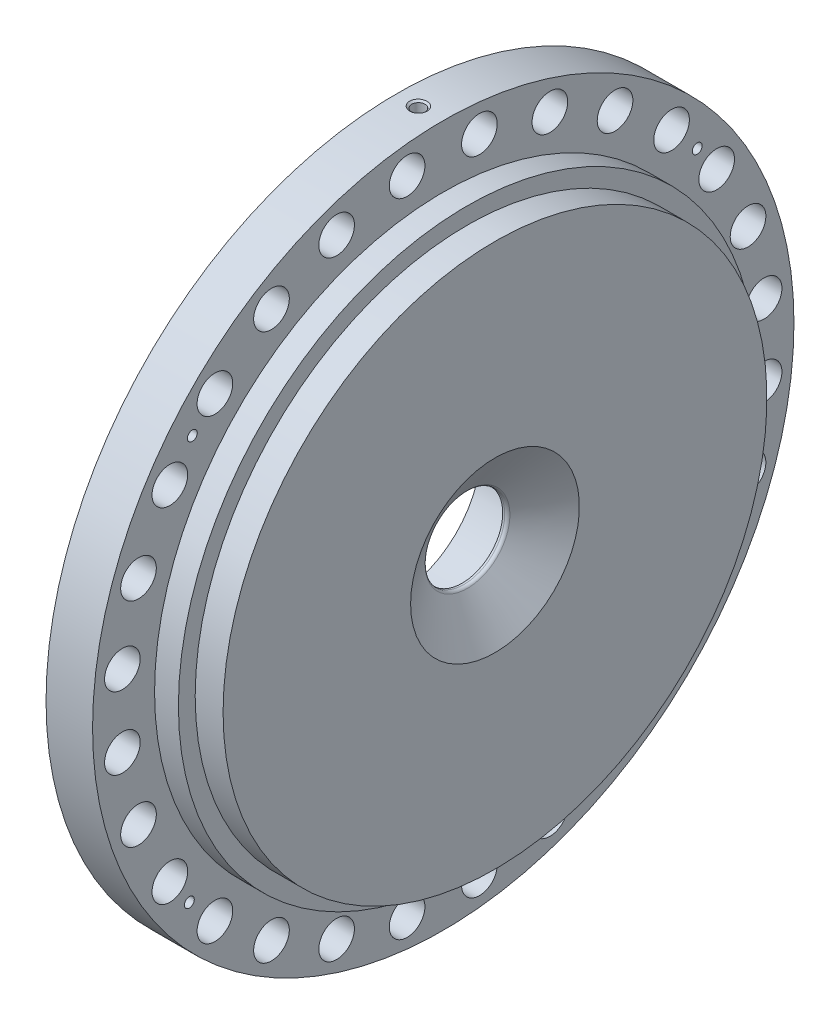
SolidWorks part; units mm, degrees
other "Markup1"
sketch "Sketch22" plane through (-5.9944, 281.051, 281.051) normal (-0.6486, 0.3883, 0.6546) x (0.7525, 0.1979, 0.6281)
material "CD4Mc-U Duplex Stainless Steel"
ref_plane "Front Plane" through (0, 0, 0) normal (0, 0, 1) x (1, 0, 0)
ref_plane "Top Plane" through (0, 0, 0) normal (0, 1, 0) x (1, 0, 0)
ref_plane "Right Plane" through (0, 0, 0) normal (1, 0, 0) x (0, 0, -1)
sketch "Sketch1" plane through (0, 0, 0) normal (0, 0, 1) x (1, 0, 0)
  line L13 (-4.7752, 67.5132) -> (-4.7752, 180.9496)
  line L14 (-4.7752, 281.051) -> (32.512, 281.051)
  line L15 (32.512, 281.051) -> (32.512, 231.3686)
  line L16 (32.512, 231.3686) -> (51.6128, 231.3686)
  line L17 (51.6128, 231.3686) -> (51.6128, 217.9066)
  line L18 (51.6128, 217.9066) -> (73.9648, 217.9066)
  line L19 (73.9648, 217.9066) -> (73.9648, 67.6275)
  line L22 (0, 0) -> (159.4613, 0) construction
  line L27 (-4.7752, 228.9937) -> (0, 228.9937)
  line L28 (0, 228.9937) -> (0, 180.9496)
  line L29 (0, 180.9496) -> (-4.7752, 180.9496)
  line L30 (-4.7752, 228.9937) -> (-4.7752, 281.051)
  line L32 (-4.7752, 67.5132) -> (47.625, 67.5132)
  line L35 (47.625, 67.5132) -> (47.625, 32.5628)
  line L36 (47.625, 32.5628) -> (49.2384, 32.5628)
  line L37 (51.8928, 33.9958) -> (73.9648, 67.6275)
  arc A0 (49.2384, 32.5628) -> (51.8928, 33.9958) centre (49.2384, 35.7378) ccw
  point P18 (50.9524, 32.5628)
  dimension "D10" = 3.175
  dimension "D1" = 78.74
  dimension "D2" = 41.4528
  dimension "D3" = 19.1008
  dimension "D4" = 3.3274
  dimension "D5" = 281.051
  dimension "D6" = 228.9937
  dimension "D7" = 231.3686
  dimension "D8" = 217.9066
  dimension "D9" = 180.9496
  dimension "D11" = 4.7752
  dimension "D12" = 32.5628
  dimension "D13" = 52.4002
  dimension "D14" = 67.5132
  dimension "D16" = 67.6275
revolve "Revolve1" add sketch "Sketch1" angle 360 about L22
sketch "Sketch4" plane through (-4.7752, 0, 0) normal (-1, 0, 0) x (0, 0, 1)
  line L0 (0, 0) -> (0, 281.051) construction
  line L1 (0, 0) -> (28.9721, 257.1355) construction
  circle A1 centre (28.9721, 257.1355) radius 14.2875
  circle A2 centre (0, 0) radius 258.7625 construction
  dimension "D2" = 28.575
  dimension "D3" = 517.525
  dimension "D1" = 6.429
extrude "Cut-Extrude1" cut sketch "Sketch4" against normal through all
pattern_circular "CirPattern2" count 28 over 360 about axis through (0, 0, 0) along (1, 0, 0) of "Cut-Extrude1"
sketch "Sketch5" plane through (0, 0, 0) normal (-1, 0, 0) x (0, 0, 1)
  line L0 (0, 0) -> (53.4138, 199.3429) construction
  line L2 (0, 0) -> (0, 281.051) construction
  circle A0 centre (0, 0) radius 206.375 construction
  circle A1 centre (53.4138, 199.3429) radius 9.525
  circle A3 centre (0, 0) radius 281.051 construction
  dimension "D1" = 412.75
  dimension "D3" = 19.05
  dimension "D2" = 15
hole_wizard "3/4-10 Tapped Hole1" positions "Sketch7" profile "Sketch8" tap size "3/4-10" standard "ANSI Inch"
sketch "Sketch7" plane through (0, 0, 0) normal (-1, 0, 0) x (0, 0, 1)
  point P0 (53.4138, 199.3429)
sketch "Sketch8" plane through (0, 199.3429, 53.4138) normal (0, 1, 0) x (0, 0, 1)
  line L0 (0, 0) -> (0, 30.4074)
  line L1 (0, 30.4074) -> (8.3337, 25.4)
  line L2 (8.3337, 25.4) -> (8.3337, 1.8263)
  line L3 (8.3337, 1.8263) -> (10.16, 0)
  line L5 (10.16, 0) -> (0, 0)
  line L6 (-8.3337, 1.8263) -> (-10.16, 0) construction
  line L10 (0, 30.4074) -> (-8.3337, 25.4) construction
  line L11 (0, -6.35) -> (0, 107.95) construction
  dimension "Tap Drill Dia." = 16.6675
  dimension "Tap Drill Depth" = 25.4
  dimension "Near C'Sink Dia." = 20.32
  dimension "Near C'Sink Angle" = 90
  dimension "Drill Angle" = 118
cosmetic thread "Hole Thread2" parameters "D1"=12.7, "D2"=19.05
pattern_circular "CirPattern3" count 12 over 360 about axis through (0, 0, 0) along (1, 0, 0) of "3/4-10 Tapped Hole1"
cosmetic thread "Hole Thread3" parameters "D1"=12.7, "D2"=19.05
cosmetic thread "Hole Thread4" parameters "D1"=12.7, "D2"=19.05
cosmetic thread "Hole Thread5" parameters "D1"=12.7, "D2"=19.05
cosmetic thread "Hole Thread6" parameters "D1"=12.7, "D2"=19.05
cosmetic thread "Hole Thread7" parameters "D1"=12.7, "D2"=19.05
cosmetic thread "Hole Thread8" parameters "D1"=12.7, "D2"=19.05
cosmetic thread "Hole Thread9" parameters "D1"=12.7, "D2"=19.05
cosmetic thread "Hole Thread10" parameters "D1"=12.7, "D2"=19.05
cosmetic thread "Hole Thread11" parameters "D1"=12.7, "D2"=19.05
cosmetic thread "Hole Thread12" parameters "D1"=12.7, "D2"=19.05
cosmetic thread "Hole Thread13" parameters "D1"=12.7, "D2"=19.05
sketch "Sketch9" plane through (-4.7752, 0, 0) normal (-1, 0, 0) x (0, 0, 1)
  line L0 (0, 0) -> (0, 94.996) construction
  line L1 (0, 0) -> (67.1723, 67.1723) construction
  circle A0 centre (0, 0) radius 94.996 construction
  circle A1 centre (67.1723, 67.1723) radius 11.1125
  dimension "D1" = 189.992
  dimension "D3" = 22.225
  dimension "D2" = 45
hole_wizard "7/8-9 Tapped Hole1" positions "3DSketch1" profile "Sketch10" tap size "7/8-9" standard "ANSI Inch"
sketch3d "3DSketch1"
  point P0 (-4.7752, 67.1723, 67.1723)
sketch "Sketch10" plane through (-4.7752, 67.1723, 67.1723) normal (0, 1, 0) x (0, 0, 1)
  line L0 (0, 0) -> (0, 31.2422)
  line L1 (0, 31.2422) -> (9.7231, 25.4)
  line L2 (9.7231, 25.4) -> (9.7231, 2.0244)
  line L3 (9.7231, 2.0244) -> (11.7475, 0)
  line L5 (11.7475, 0) -> (0, 0)
  line L6 (-9.7231, 2.0244) -> (-11.7475, 0) construction
  line L10 (0, 31.2422) -> (-9.7231, 25.4) construction
  line L11 (0, -6.35) -> (0, 107.95) construction
  dimension "Tap Drill Dia." = 19.4462
  dimension "Tap Drill Depth" = 25.4
  dimension "Near C'Sink Dia." = 23.495
  dimension "Near C'Sink Angle" = 90
  dimension "Drill Angle" = 118
cosmetic thread "Hole Thread14" parameters "D1"=44.45, "D2"=22.225
pattern_circular "CirPattern4" count 4 over 360 about axis through (0, 0, 0) along (1, 0, 0) of "7/8-9 Tapped Hole1"
cosmetic thread "Hole Thread15" parameters "D1"=44.45, "D2"=22.225
cosmetic thread "Hole Thread16" parameters "D1"=44.45, "D2"=22.225
cosmetic thread "Hole Thread17" parameters "D1"=44.45, "D2"=22.225
sketch "Sketch11" plane through (-4.7752, 0, 0) normal (-1, 0, 0) x (0, 0, 1)
  line L0 (0, 0) -> (201.0962, 162.8445) construction
  line L1 (0, 0) -> (258.7625, 0) construction
  circle A0 centre (0, 0) radius 258.7625 construction
  circle A2 centre (201.0962, 162.8445) radius 4.7625
  dimension "D1" = 517.525
  dimension "D3" = 9.525
  dimension "D2" = 39
hole_wizard "Tap Drill for 3/8-16 Tap1" positions "3DSketch9" profile "Sketch21" hole size "3/8-16" standard "ANSI Inch"
sketch3d "3DSketch9"
  point P0 (-4.7752, 162.8445, 201.0962)
sketch "Sketch21" plane through (-4.7752, 162.8445, 201.0962) normal (0, 1, 0) x (0, 0, 1)
  line L0 (0, 0) -> (0, 43.0247)
  line L1 (0, 43.0247) -> (3.9687, 40.64)
  line L2 (3.9687, 40.64) -> (3.9687, 0.635)
  line L3 (3.9687, 0.635) -> (4.6037, 0)
  line L5 (4.6037, 0) -> (0, 0)
  line L6 (-3.9687, 0.635) -> (-4.6037, 0) construction
  line L10 (0, 43.0247) -> (-3.9688, 40.64) construction
  line L11 (0, -6.35) -> (0, 107.95) construction
  dimension "Hole Dia." = 7.9375
  dimension "Hole Depth" = 40.64
  dimension "Near C'Sink Dia." = 9.2075
  dimension "Near C'Sink Angle" = 90
  dimension "Drill Angle" = 118
ref_plane "Plane2" through (0, 281.051, 0) normal (0, 1, 0) x (1, 0, 0)
sketch "Sketch20" plane through (0, 281.051, 0) normal (0, 1, 0) x (1, 0, 0)
  line L0 (-4.7752, 0) -> (12.5984, 0) construction
  line L1 (-4.7752, 281.051) -> (-4.7752, -281.051) construction
  dimension "D1" = 17.3736
pattern_circular "CirPattern5" count 56 over 360 about axis through (0, 0, 0) along (-1, 0, 0) skipping 1, 2, 3, 4, 5, 6, 7, 8, 9, 10, 11, 12, 13, 14, 15, 17, 18, 19, 20, 21, 22, 23, 24, 25, 26, 27, 29, 30, 31, 32, 33, 34, 35, 36, 37, 38, 39, 40, 41, 42, 43, 45, 46, 47, 48, 49, 50, 51, 52, 53, 54, 55 of "Tap Drill for 3/8-16 Tap1"
hole_wizard "1/2-13 Tapped Hole4" positions "3DSketch8" profile "Sketch19" tap size "1/2-13" standard "ANSI Inch"
sketch3d "3DSketch8"
  point P0 (12.5984, 281.051, 0)
sketch "Sketch19" plane through (12.5984, 281.051, 0) normal (1, 0, 0) x (0, 0, 1)
  line L0 (0, 0) -> (0, 38.2715)
  line L1 (0, 38.2715) -> (5.3581, 35.052)
  line L2 (5.3581, 35.052) -> (5.3581, 1.3651)
  line L3 (5.3581, 1.3651) -> (6.985, 0)
  line L5 (6.985, 0) -> (0, 0)
  line L6 (-5.3581, 1.3651) -> (-6.985, 0) construction
  line L10 (0, 38.2715) -> (-5.3581, 35.052) construction
  line L11 (0, -6.35) -> (0, 107.95) construction
  dimension "Tap Drill Dia." = 10.7163
  dimension "Tap Drill Depth" = 35.052
  dimension "Near C'Sink Dia." = 13.97
  dimension "Near C'Sink Angle" = 100
  dimension "Drill Angle" = 118
cosmetic thread "Hole Thread24" parameters "D1"=25.4, "D2"=12.7
